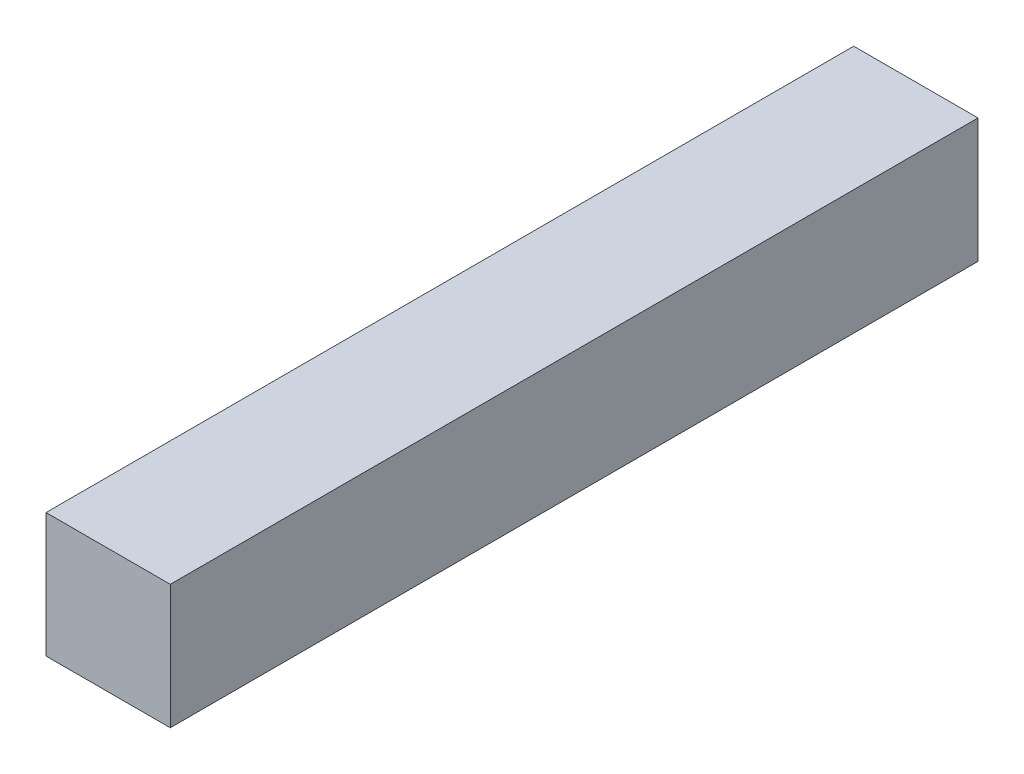
SolidWorks part; units mm, degrees
ref_plane "Front Plane" through (0, 0, 0) normal (0, 0, 1) x (1, 0, 0)
ref_plane "Top Plane" through (0, 0, 0) normal (0, 1, 0) x (1, 0, 0)
ref_plane "Right Plane" through (0, 0, 0) normal (1, 0, 0) x (0, 0, -1)
sketch "Sketch1" plane through (0, 0, 0) normal (0, 0, 1) x (1, 0, 0)
  line L1 (12.7, -12.7) -> (-12.7, -12.7)
  line L2 (12.7, -12.7) -> (12.7, 12.7)
  line L3 (12.7, 12.7) -> (-12.7, 12.7)
  line L4 (-12.7, -12.7) -> (-12.7, 12.7)
  line L5 (12.7, -12.7) -> (-12.7, 12.7) construction
  line L6 (12.7, 12.7) -> (-12.7, -12.7) construction
  point P0 (0, 0)
  dimension "D1" = 25.4
extrude "Boss-Extrude1" add sketch "Sketch1" along normal blind 165.1
